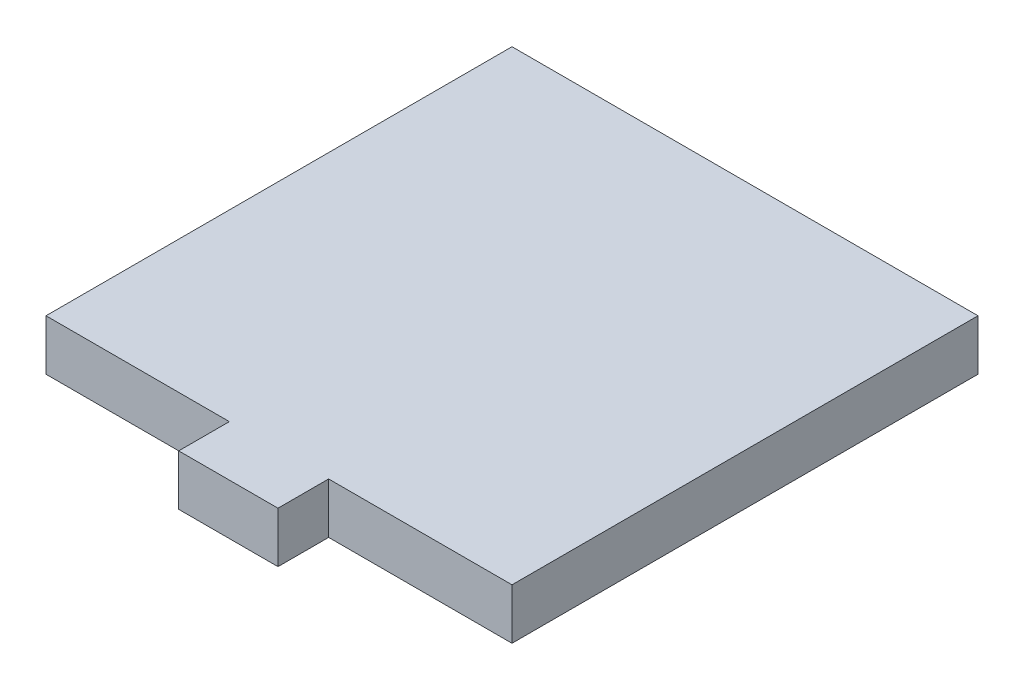
SolidWorks part; units mm, degrees
ref_plane "Front Plane" through (0, 0, 0) normal (0, 0, 1) x (1, 0, 0)
ref_plane "Top Plane" through (0, 0, 0) normal (0, 1, 0) x (1, 0, 0)
ref_plane "Right Plane" through (0, 0, 0) normal (1, 0, 0) x (0, 0, -1)
sketch "Sketch1" plane through (0, 0, 0) normal (0, 1, 0) x (1, 0, 0)
  line L1 (-14.605, 14.605) -> (14.605, 14.605)
  line L2 (-14.605, 14.605) -> (-14.605, -14.605)
  line L3 (-14.605, -14.605) -> (14.605, -14.605)
  line L4 (14.605, 14.605) -> (14.605, -14.605)
  line L5 (-14.605, 14.605) -> (14.605, -14.605) construction
  line L6 (-14.605, -14.605) -> (14.605, 14.605) construction
  point P0 (0, 0)
  dimension "D1" = 29.21
  dimension "D2" = 29.21
extrude "Boss-Extrude1" add sketch "Sketch1" along normal blind 3.175
sketch "Sketch2" plane through (0, 0, 14.605) normal (0, 0, 1) x (1, 0, 0)
  line L0 (-14.605, 3.175) -> (14.605, 3.175) construction
  line L1 (3.1115, 3.175) -> (-3.1115, 3.175)
  line L2 (3.1115, 3.175) -> (3.1115, 0)
  line L3 (3.1115, 0) -> (-3.1115, 0)
  line L4 (-3.1115, 3.175) -> (-3.1115, 0)
  line L5 (-14.605, 0) -> (14.605, 0) construction
  line L6 (3.1115, 3.175) -> (14.605, 3.175) construction
  line L7 (-3.1115, 3.175) -> (-14.605, 3.175) construction
  dimension "D1" = 6.223
extrude "Boss-Extrude2" add sketch "Sketch2" along normal blind 3.175
